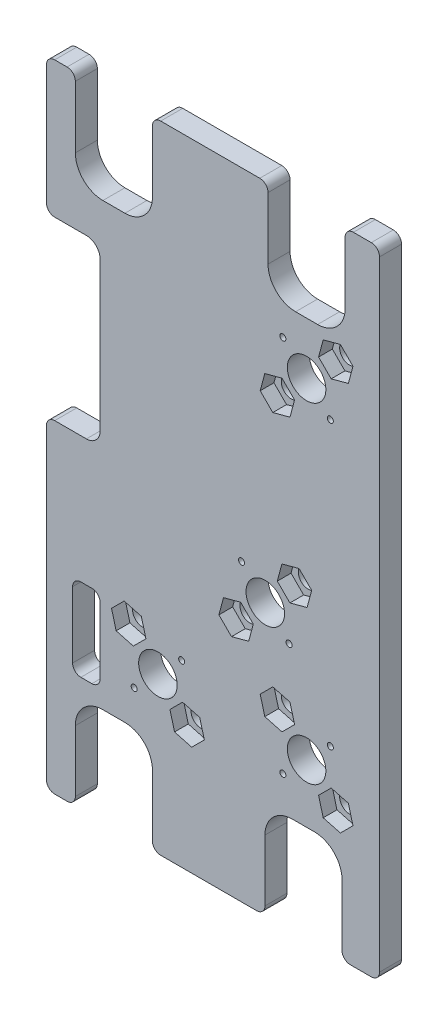
SolidWorks part; units mm, degrees
ref_plane "Top Plane" through (0, 0, 0) normal (0, 0, 1) x (1, 0, 0)
ref_plane "Right Plane" through (0, 0, 0) normal (0, 1, 0) x (1, 0, 0)
ref_plane "Front Plane" through (0, 0, 0) normal (1, 0, 0) x (0, 0, -1)
sketch "Sketch1" plane through (0, 0, 0) normal (0, 0, 1) x (1, 0, 0)
  line L0 (7, -90.81) -> (7, -83.19) construction
  line L1 (7, -52.81) -> (7, -45.19) construction
  line L2 (7, -35.81) -> (7, -28.19) construction
  line L3 (5.0001, -111.6) -> (5.0001, -115.25)
  line L4 (9.5, -79.5) -> (4.5, -79.5)
  line L5 (9.5, -79.5) -> (9.5, -94.5)
  line L6 (9.5, -94.5) -> (4.5, -94.5)
  line L7 (4.5, -79.5) -> (4.5, -94.5)
  line L8 (9.5, -79.5) -> (4.5, -94.5) construction
  line L9 (9.5, -94.5) -> (4.5, -79.5) construction
  line L10 (9.5, -41.5) -> (4.5, -41.5) construction
  line L11 (9.5, -41.5) -> (9.5, -56.5)
  line L12 (9.5, -56.5) -> (4.5, -56.5)
  line L13 (4.5, -41.5) -> (4.5, -56.5) construction
  line L14 (9.5, -41.5) -> (4.5, -56.5) construction
  line L15 (9.5, -56.5) -> (4.5, -41.5) construction
  line L16 (9.5, -24.5) -> (4.5, -24.5)
  line L17 (9.5, -24.5) -> (9.5, -39.5) construction
  line L18 (9.5, -39.5) -> (4.5, -39.5) construction
  line L19 (4.5, -24.5) -> (4.5, -39.5) construction
  line L20 (9.5, -24.5) -> (4.5, -39.5) construction
  line L21 (9.5, -39.5) -> (4.5, -24.5) construction
  line L22 (5.0001, -111.6) -> (19.0001, -111.6) construction
  line L23 (5.0001, -111.6) -> (5.0001, -97.6)
  line L24 (5.0001, -97.6) -> (19.0001, -97.6)
  line L25 (19.0001, -111.6) -> (19.0001, -97.6)
  line L26 (5.0001, -111.6) -> (19.0001, -97.6) construction
  line L27 (5.0001, -97.6) -> (19.0001, -111.6) construction
  line L28 (53.4351, -111.6) -> (39.4351, -111.6) construction
  line L29 (53.4351, -111.6) -> (53.4351, -97.6)
  line L30 (53.4351, -97.6) -> (39.4351, -97.6)
  line L31 (39.4351, -111.6) -> (39.4351, -97.6)
  line L32 (53.4351, -111.6) -> (39.4351, -97.6) construction
  line L33 (53.4351, -97.6) -> (39.4351, -111.6) construction
  line L34 (5.0001, -3.5001) -> (19.0001, -3.5001) construction
  line L35 (5.0001, -3.5001) -> (5.0001, -17.5001)
  line L36 (5.0001, -17.5001) -> (19.0001, -17.5001)
  line L37 (19.0001, -3.5001) -> (19.0001, -17.5001)
  line L38 (5.0001, -3.5001) -> (19.0001, -17.5001) construction
  line L39 (5.0001, -17.5001) -> (19.0001, -3.5001) construction
  line L40 (54.0001, -3.5001) -> (40.0001, -3.5001) construction
  line L41 (54.0001, -3.5001) -> (54.0001, -17.5001)
  line L42 (54.0001, -17.5001) -> (40.0001, -17.5001)
  line L43 (40.0001, -3.5001) -> (40.0001, -17.5001)
  line L44 (54.0001, -3.5001) -> (40.0001, -17.5001) construction
  line L45 (54.0001, -17.5001) -> (40.0001, -3.5001) construction
  line L47 (19.0001, -111.6) -> (19.0001, -115.25)
  line L49 (39.4351, -111.6) -> (39.4351, -115.25)
  line L51 (53.4351, -111.6) -> (53.4351, -115.25)
  line L53 (40.0001, -3.5001) -> (40.0001, 0.25)
  line L55 (54.0001, -3.5001) -> (54.0001, 0.25)
  line L57 (5.0001, -3.5001) -> (5.0001, 0.25)
  line L59 (19.0001, -3.5001) -> (19.0001, 0.25)
  line L61 (60.25, -112.0139) -> (60.25, -2.9861) construction
  line L62 (-0.25, -115.25) -> (5.0001, -115.25)
  line L63 (-0.25, -115.25) -> (-0.25, -56.5)
  line L64 (-0.25, 0.25) -> (5.0001, 0.25)
  line L65 (60.25, -115.25) -> (60.25, 0.25)
  line L67 (35.7, -115.25) -> (60.25, -115.25) construction
  line L68 (-0.25, -71.962) -> (-0.25, -112.0139) construction
  line L69 (22.9, 0.25) -> (-0.25, 0.25) construction
  line L70 (4.5, -56.5) -> (-0.25, -56.5)
  line L71 (4.5, -24.5) -> (-0.25, -24.5)
  line L72 (9.5, -56.5) -> (9.5, -24.5)
  line L73 (-0.25, -24.5) -> (-0.25, 0.25)
  line L74 (53.4351, -115.25) -> (60.25, -115.25)
  line L75 (19.0001, -115.25) -> (39.4351, -115.25)
  line L76 (19.0001, 0.25) -> (40.0001, 0.25)
  line L77 (54.0001, 0.25) -> (60.25, 0.25)
  circle A0 centre (15.6866, -91.3134) radius 1.3 construction
  circle A1 centre (24.3133, -82.6867) radius 1.3 construction
  circle A2 centre (42.6866, -91.3134) radius 1.3 construction
  circle A3 centre (51.3133, -82.6867) radius 1.3 construction
  circle A4 centre (35.1866, -61.6867) radius 1.3 construction
  circle A5 centre (43.8133, -70.3134) radius 1.3 construction
  circle A6 centre (42.6866, -22.6867) radius 1.3 construction
  circle A7 centre (51.3133, -31.3134) radius 1.3 construction
  circle A8 centre (15.6866, -91.3134) radius 1.3 construction
  circle A9 centre (24.3133, -82.6867) radius 1.3 construction
  circle A10 centre (42.6866, -91.3134) radius 1.3 construction
  circle A11 centre (51.3133, -82.6867) radius 1.3 construction
  circle A12 centre (35.1866, -61.6867) radius 1.3 construction
  circle A13 centre (43.8133, -70.3134) radius 1.3 construction
  circle A14 centre (42.6866, -22.6867) radius 1.3 construction
  circle A15 centre (51.3133, -31.3134) radius 1.3 construction
  circle A16 centre (12.0001, -10.5001) radius 4.75 construction
  circle A17 centre (47.0001, -10.5001) radius 4.75 construction
  circle A18 centre (12.0001, -104.6) radius 4.75 construction
  circle A19 centre (46.4351, -104.6) radius 4.75 construction
  circle A20 centre (12.0001, -10.5001) radius 4.75 construction
  circle A21 centre (47.0001, -10.5001) radius 4.75 construction
  circle A22 centre (12.0001, -104.6) radius 4.75 construction
  circle A23 centre (46.4351, -104.6) radius 4.75 construction
  circle A24 centre (7, -45.19) radius 0.6 construction
  circle A25 centre (7, -52.81) radius 0.6 construction
  circle A26 centre (7, -35.81) radius 0.6 construction
  circle A27 centre (7, -28.19) radius 0.6 construction
  circle A28 centre (7, -45.19) radius 0.6
  circle A29 centre (7, -52.81) radius 0.6
  circle A30 centre (7, -35.81) radius 0.6
  circle A31 centre (7, -28.19) radius 0.6
  circle A32 centre (7, -28.19) radius 0.6
  circle A33 centre (7, -90.81) radius 0.6 construction
  circle A34 centre (7, -83.19) radius 0.6 construction
  circle A35 centre (7, -90.81) radius 0.6
  circle A36 centre (7, -83.19) radius 0.6
  circle A37 centre (19.9999, -87) radius 3.25 construction
  circle A38 centre (46.9999, -87) radius 3.25 construction
  circle A39 centre (39.4999, -66) radius 3.25 construction
  circle A40 centre (46.9999, -27) radius 3.25 construction
  circle A41 centre (19.9999, -87) radius 3.25 construction
  circle A42 centre (46.9999, -87) radius 3.25 construction
  circle A43 centre (39.4999, -66) radius 3.25 construction
  circle A44 centre (46.9999, -27) radius 3.25 construction
  circle A45 centre (46.9999, -27) radius 3.5
  circle A46 centre (39.4999, -66) radius 3.5
  circle A47 centre (46.9999, -87) radius 3.5
  circle A48 centre (19.9999, -87) radius 3.5
  circle A49 centre (42.6866, -22.6867) radius 0.55
  circle A50 centre (51.3133, -31.3134) radius 0.55
  circle A51 centre (43.8133, -70.3134) radius 0.55
  circle A52 centre (35.1866, -61.6867) radius 0.55
  circle A53 centre (51.3133, -82.6867) radius 0.55
  circle A54 centre (42.6866, -91.3134) radius 0.55
  circle A55 centre (24.3133, -82.6867) radius 0.55
  circle A56 centre (15.6866, -91.3134) radius 0.55
  point P91 (7, -87)
  point P96 (7, -49)
  point P101 (7, -32)
  dimension "D3" = 5
  dimension "D4" = 15
  dimension "D5" = 14
  dimension "D1" = 0.25
  dimension "D2" = 0.75
extrude "Boss-Extrude1" add sketch "Sketch1" along normal blind 4 contours L77 L55 L41 L42 L43 L53 L76 L59 L37 L36 L35 L57 L64 L73 L71 L16 L72 L11 L12 L70 L63 L62 L3 L23 L24 L25 L47 L75 L49 L31 L30 L29 L51 L74 L65 A56 A55 A54 A53 A52 A51 A50 A49
sketch "Sketch2" plane through (0, 0, 4) normal (0, 0, 1) x (1, 0, 0)
  line L0 (14.6966, -81.6967) -> (25.3032, -92.3033) construction
  line L1 (52.3032, -92.3033) -> (41.6966, -81.6967) construction
  line L2 (26.14, -95.4263) -> (28.4262, -93.1402)
  line L3 (28.4262, -93.1402) -> (27.5894, -90.0172)
  line L4 (27.5894, -90.0172) -> (24.4664, -89.1804)
  line L5 (24.4664, -89.1804) -> (22.1802, -91.4665)
  line L6 (22.1802, -91.4665) -> (23.017, -94.5895)
  line L7 (23.017, -94.5895) -> (26.14, -95.4263)
  line L8 (13.8598, -78.5738) -> (11.5736, -80.8599)
  line L9 (11.5736, -80.8599) -> (12.4104, -83.9829)
  line L10 (12.4104, -83.9829) -> (15.5334, -84.8197)
  line L11 (15.5334, -84.8197) -> (17.8196, -82.5336)
  line L12 (17.8196, -82.5336) -> (16.9828, -79.4106)
  line L13 (16.9828, -79.4106) -> (13.8598, -78.5738)
  line L14 (44.8032, -60.6967) -> (34.1966, -71.3033) construction
  line L15 (52.3032, -21.6967) -> (41.6966, -32.3033) construction
  line L16 (15.6866, -91.3134) -> (24.3133, -82.6867) construction
  line L17 (53.14, -95.4263) -> (55.4262, -93.1402)
  line L18 (55.4262, -93.1402) -> (54.5894, -90.0172)
  line L19 (54.5894, -90.0172) -> (51.4664, -89.1804)
  line L20 (51.4664, -89.1804) -> (49.1802, -91.4665)
  line L21 (49.1802, -91.4665) -> (50.017, -94.5895)
  line L22 (50.017, -94.5895) -> (53.14, -95.4263)
  line L23 (38.5736, -80.8599) -> (39.4104, -83.9829)
  line L24 (39.4104, -83.9829) -> (42.5334, -84.8197)
  line L25 (42.5334, -84.8197) -> (44.8196, -82.5336)
  line L26 (44.8196, -82.5336) -> (43.9828, -79.4106)
  line L27 (43.9828, -79.4106) -> (40.8598, -78.5738)
  line L28 (40.8598, -78.5738) -> (38.5736, -80.8599)
  line L29 (31.0736, -72.1402) -> (33.3598, -74.4263)
  line L30 (33.3598, -74.4263) -> (36.4828, -73.5895)
  line L31 (36.4828, -73.5895) -> (37.3196, -70.4665)
  line L32 (37.3196, -70.4665) -> (35.0334, -68.1804)
  line L33 (35.0334, -68.1804) -> (31.9104, -69.0172)
  line L34 (31.9104, -69.0172) -> (31.0736, -72.1402)
  line L35 (47.9262, -59.8599) -> (45.64, -57.5738)
  line L36 (45.64, -57.5738) -> (42.517, -58.4106)
  line L37 (42.517, -58.4106) -> (41.6802, -61.5336)
  line L38 (41.6802, -61.5336) -> (43.9664, -63.8197)
  line L39 (43.9664, -63.8197) -> (47.0894, -62.9829)
  line L40 (47.0894, -62.9829) -> (47.9262, -59.8599)
  line L41 (44.8196, -31.4665) -> (42.5334, -29.1804)
  line L42 (42.5334, -29.1804) -> (39.4104, -30.0172)
  line L43 (39.4104, -30.0172) -> (38.5736, -33.1402)
  line L44 (38.5736, -33.1402) -> (40.8598, -35.4263)
  line L45 (40.8598, -35.4263) -> (43.9828, -34.5895)
  line L46 (43.9828, -34.5895) -> (44.8196, -31.4665)
  line L47 (54.5894, -23.9829) -> (55.4262, -20.8599)
  line L48 (55.4262, -20.8599) -> (53.14, -18.5738)
  line L49 (53.14, -18.5738) -> (50.017, -19.4106)
  line L50 (50.017, -19.4106) -> (49.1802, -22.5336)
  line L51 (49.1802, -22.5336) -> (51.4664, -24.8197)
  line L52 (51.4664, -24.8197) -> (54.5894, -23.9829)
  line L53 (42.6866, -91.3134) -> (51.3133, -82.6867) construction
  line L54 (35.1866, -61.6867) -> (43.8133, -70.3134) construction
  line L55 (42.6866, -22.6867) -> (51.3133, -31.3134) construction
  circle A0 centre (25.3032, -92.3033) radius 2.8 construction
  circle A1 centre (14.6966, -81.6967) radius 2.8 construction
  circle A3 centre (19.9999, -87) radius 3.5 construction
  circle A4 centre (46.9999, -87) radius 3.5 construction
  circle A5 centre (39.4999, -66) radius 3.5 construction
  circle A6 centre (46.9999, -27) radius 3.5 construction
  circle A7 centre (52.3032, -92.3033) radius 2.8 construction
  circle A8 centre (41.6966, -81.6967) radius 2.8 construction
  circle A9 centre (34.1966, -71.3033) radius 2.8 construction
  circle A10 centre (44.8032, -60.6967) radius 2.8 construction
  circle A11 centre (41.6966, -32.3033) radius 2.8 construction
  circle A12 centre (52.3032, -21.6967) radius 2.8 construction
  circle A13 centre (52.3032, -92.3033) radius 1.8
  circle A14 centre (41.6966, -81.6967) radius 1.8
  circle A15 centre (34.1966, -71.3033) radius 1.8
  circle A16 centre (44.8032, -60.6967) radius 1.8
  circle A17 centre (14.6966, -81.6967) radius 1.8
  circle A18 centre (25.3032, -92.3033) radius 1.8
  circle A19 centre (52.3032, -21.6967) radius 1.8
  circle A20 centre (41.6966, -32.3033) radius 1.8
  point P4 (19.9999, -87)
  point P23 (39.4999, -56.9143)
  point P24 (46.9999, -87)
  point P28 (39.4999, -66)
  point P32 (46.9999, -27)
  point P104 (47.6609, -19.5108)
  point P105 (46.7999, -19.5897)
  point P106 (47.459, -19.5141)
  point P107 (47.459, -19.5141)
  point P108 (42.5756, -42.4994)
  dimension "D2" = 5.6
  dimension "D3" = 3.6
  dimension "D1" = 15
extrude "Cut-Extrude1" cut sketch "Sketch2" against normal blind 2.5
sketch "Sketch4" plane through (0, 0, 4) normal (0, 0, 1) x (1, 0, 0)
  circle A0 centre (52.3032, -21.6967) radius 1.8 construction
  circle A1 centre (41.6966, -32.3033) radius 1.8 construction
  circle A2 centre (44.8032, -60.6967) radius 1.8 construction
  circle A3 centre (34.1966, -71.3033) radius 1.8 construction
  circle A4 centre (41.6966, -81.6967) radius 1.8 construction
  circle A5 centre (52.3032, -92.3033) radius 1.8 construction
  circle A6 centre (25.3032, -92.3033) radius 1.8 construction
  circle A7 centre (14.6966, -81.6967) radius 1.8 construction
  circle A8 centre (52.3032, -21.6967) radius 1.8
  circle A9 centre (41.6966, -32.3033) radius 1.8
  circle A10 centre (44.8032, -60.6967) radius 1.8
  circle A11 centre (34.1966, -71.3033) radius 1.8
  circle A12 centre (41.6966, -81.6967) radius 1.8
  circle A13 centre (52.3032, -92.3033) radius 1.8
  circle A14 centre (25.3032, -92.3033) radius 1.8
  circle A15 centre (14.6966, -81.6967) radius 1.8
extrude "Cut-Extrude2" cut sketch "Sketch4" against normal through all
fillet "Fillet1" radius 5 8 edges at (5.0001, -17.5001, 2) (19.0001, -17.5001, 2) (54.0001, -17.5001, 2) (40.0001, -17.5001, 2) (53.4351, -97.6, 2) (39.4351, -97.6, 2) (19.0001, -97.6, 2) (5.0001, -97.6, 2)
fillet "Fillet2" radius 2.5 2 edges at (9.5, -56.5, 2) (9.5, -24.5, 2)
fillet "Fillet3" radius 1.5 4 edges at (4.5, -79.5, 2) (9.5, -79.5, 2) (9.5, -94.5, 2) (4.5, -94.5, 2)
fillet "Fillet4" radius 1.5 14 edges at (-0.25, -115.25, 2) (5.0001, -115.25, 2) (19.0001, -115.25, 2) (39.4351, -115.25, 2) (53.4351, -115.25, 2) (60.25, -115.25, 2) (60.25, 0.25, 2) (54.0001, 0.25, 2) (40.0001, 0.25, 2) (19.0001, 0.25, 2) (5.0001, 0.25, 2) (-0.25, 0.25, 2) (-0.25, -24.5, 2) (-0.25, -56.5, 2)
